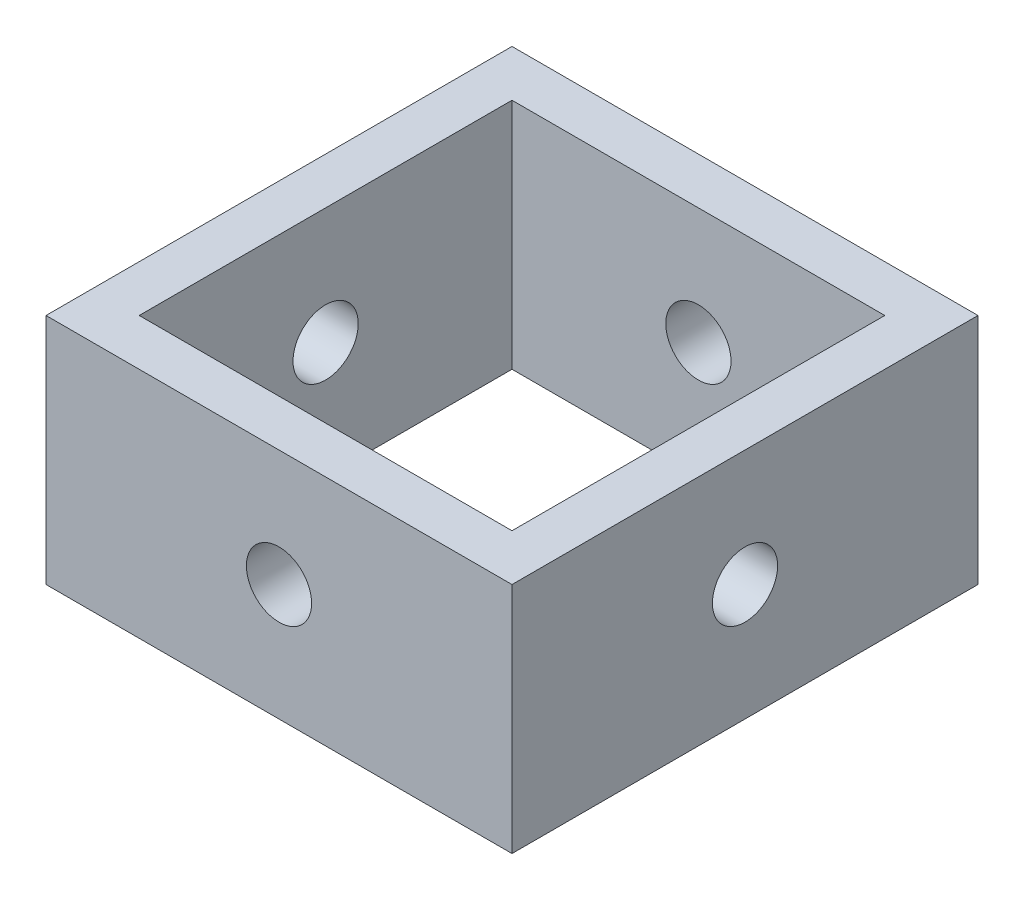
SolidWorks part; units mm, degrees
ref_plane "Front Plane" through (0, 0, 0) normal (0, 0, 1) x (1, 0, 0)
ref_plane "Top Plane" through (0, 0, 0) normal (0, 1, 0) x (1, 0, 0)
ref_plane "Right Plane" through (0, 0, 0) normal (1, 0, 0) x (0, 0, -1)
sketch "Sketch1" plane through (0, 0, 0) normal (0, 1, 0) x (1, 0, 0)
  line L0 (20, -20) -> (20, 20)
  line L1 (-25, -25) -> (25, -25)
  line L2 (-25, -25) -> (-25, 25)
  line L3 (-25, 25) -> (25, 25)
  line L4 (25, -25) -> (25, 25)
  line L5 (-25, -25) -> (25, 25) construction
  line L6 (-25, 25) -> (25, -25) construction
  line L7 (-20, 20) -> (20, 20)
  line L8 (-20, -20) -> (-20, 20)
  line L9 (-20, -20) -> (20, -20)
  point P0 (0, 0)
  dimension "D1" = 50
  dimension "D2" = 50
  dimension "D3" = 5
extrude "Boss-Extrude1" add sketch "Sketch1" along normal blind 25
sketch "Sketch2" plane through (25, 0, 0) normal (1, 0, 0) x (0, 0, -1)
  line L0 (-25, 0) -> (25, 0) construction
  line L1 (25, 25) -> (25, 0) construction
  circle A0 centre (0, 12.5) radius 3.5
  dimension "D3" = 7
  dimension "D1" = 12.5
  dimension "D2" = 25
extrude "Cut-Extrude1" cut sketch "Sketch2" against normal blind 55
sketch "Sketch3" plane through (0, 0, 25) normal (0, 0, 1) x (1, 0, 0)
  line L0 (-25, 0) -> (25, 0) construction
  line L1 (25, 25) -> (25, 0) construction
  circle A0 centre (0, 12.5) radius 3.5
  dimension "D3" = 7
  dimension "D1" = 12.5
  dimension "D2" = 25
extrude "Cut-Extrude2" cut sketch "Sketch3" against normal blind 55
